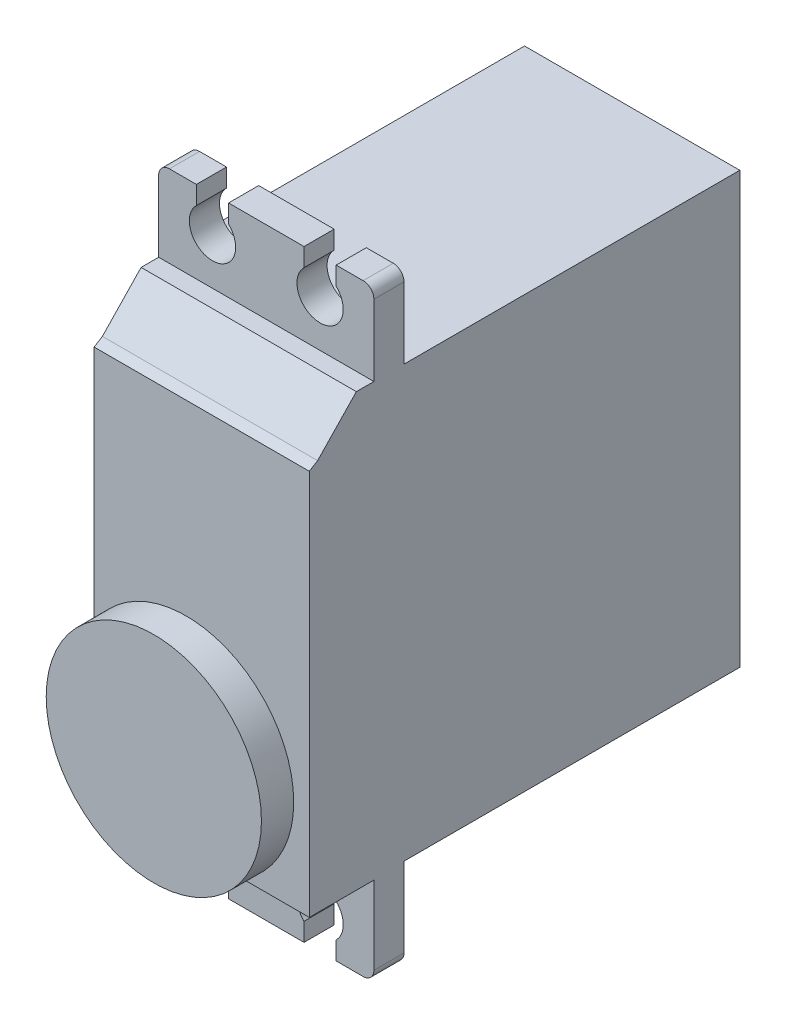
SolidWorks part; units mm, degrees
ref_plane "Front Plane" through (0, 0, 0) normal (0, 0, 1) x (1, 0, 0)
ref_plane "Top Plane" through (0, 0, 0) normal (0, 1, 0) x (1, 0, 0)
ref_plane "Right Plane" through (0, 0, 0) normal (1, 0, 0) x (0, 0, -1)
other "Configuration Table"
sketch "Sketch1" plane through (0, 0, 0) normal (0, 0, 1) x (1, 0, 0)
  line L0 (21.2784, 18.3365) -> (21.2784, 49.5365) construction
  line L1 (111.0279, 66.698) -> (111.0279, 64.6041) construction
  line L2 (101.0279, 10.698) -> (121.0279, 10.698)
  line L3 (101.0279, 10.698) -> (101.0279, 66.698)
  line L4 (101.0279, 66.698) -> (121.0279, 66.698)
  line L5 (121.0279, 10.698) -> (121.0279, 66.698)
  line L6 (101.0279, 38.698) -> (94.5146, 38.698) construction
  line L7 (106.0279, 13.948) -> (106.0279, 28.948) construction
  line L8 (111.0279, 10.698) -> (111.0279, 28.948) construction
  line L9 (106.0279, 28.948) -> (111.0279, 28.948) construction
  line L10 (104.5342, 10.698) -> (104.5342, 12.4)
  line L11 (107.5217, 10.698) -> (107.5217, 12.4)
  line L12 (114.5342, 10.698) -> (114.5342, 12.4)
  line L13 (117.5217, 10.698) -> (117.5217, 12.4)
  line L14 (104.5342, 66.698) -> (104.5342, 64.996)
  line L15 (107.5217, 66.698) -> (107.5217, 64.996)
  line L16 (114.5342, 66.698) -> (114.5342, 64.996)
  line L17 (117.5217, 66.698) -> (117.5217, 64.996)
  circle A0 centre (106.0279, 63.448) radius 2.1512
  circle A1 centre (116.0279, 63.448) radius 2.1512
  circle A2 centre (116.0279, 13.948) radius 2.1512
  circle A3 centre (106.0279, 13.948) radius 2.1512
  circle A4 centre (111.0279, 28.948) radius 2.7114
  line B0 (25.5393, 52.2674) -> (25.5393, 53.836)
  line B1 (30.5611, 18.2674) -> (70.5611, 18.2674)
  line B2 (30.5611, 18.2674) -> (30.5611, 49.4674)
  line B3 (30.5611, 49.4674) -> (70.5611, 49.4674)
  line B4 (70.5611, 18.2674) -> (70.5611, 49.4674)
  line B5 (25.5393, 53.836) -> (30.5611, 53.836)
  line B6 (30.5611, 53.836) -> (30.5611, 53.9)
  line B7 (30.5611, 53.9) -> (34.3144, 57.4974)
  line B8 (34.3144, 57.4974) -> (34.7849, 58.2674)
  line B9 (34.7849, 58.2674) -> (54.0071, 58.2674)
  line B10 (54.0071, 58.2674) -> (54.5684, 59.186)
  line B11 (54.5684, 59.186) -> (57.2514, 59.186)
  line B12 (57.2514, 59.186) -> (57.2514, 62.7174)
  line B13 (57.2514, 62.7174) -> (63.6958, 62.7174)
  line B14 (63.6958, 62.7174) -> (63.6958, 59.186)
  line B15 (63.6958, 59.186) -> (66.0527, 59.186)
  line B16 (66.0527, 59.186) -> (66.9468, 58.2674)
  line B17 (66.9468, 58.2674) -> (70.6846, 58.2674)
  line B18 (70.6846, 58.2674) -> (70.6846, 53.2324)
  line B19 (70.6846, 53.2324) -> (75.9568, 53.2324)
  line B20 (75.9568, 53.2324) -> (75.9568, 52.1823)
  line B21 (75.9568, 52.1823) -> (78.9446, 52.1823)
  line B22 (78.9446, 52.1823) -> (78.9446, 49.4674)
  line B23 (78.9446, 49.4674) -> (70.5611, 49.4674)
  line B24 (25.5393, 52.2674) -> (22.5513, 52.2674)
  line B25 (22.5513, 52.2674) -> (22.5513, 49.4674)
  line B26 (22.5513, 49.4674) -> (30.5611, 49.4674)
  dimension "D1" = 31.2
  dimension "D2" = 56
  dimension "D3" = 20
  dimension "D4" = 49.5
  dimension "D5" = 10
  dimension "D6" = 15
sketch_block_instance "Block1-1"
sketch_block "Block1" parameters "D1"=31.2, "D2"=2.8, "D3"=40, "D4"=44.45, "D5"=40.3776
extrude "Boss-Extrude2" add sketch "Sketch1" along normal blind 2.8 contours L10 A3 L11 L2 L12 A2 L13 L5 L4 L17 A1 L16 L15 A0 L14 L3 A4
fillet "Fillet1" radius 1 4 edges at (101.0279, 10.698, 1.4) (121.0279, 10.698, 1.4) (121.0279, 66.698, 1.4) (101.0279, 66.698, 1.4)
sketch "Sketch5" plane through (101.0279, 0, 0) normal (-1, 0, 0) x (0, 0, 1)
  line L3 (2.8, 10.698) -> (0, 10.698) construction
  line L4 (0, 10.698) -> (0, 66.698) construction
  line B0 (2.8, 64.1033) -> (4.3686, 64.1033)
  line B1 (-31.2, 59.0816) -> (-31.2, 19.0816)
  line B2 (-31.2, 59.0816) -> (0, 59.0816)
  line B3 (0, 59.0816) -> (0, 19.0816)
  line B4 (-31.2, 19.0816) -> (0, 19.0816)
  line B5 (4.3686, 64.1033) -> (4.3686, 59.0816)
  line B6 (4.3686, 59.0816) -> (4.4326, 59.0816)
  line B7 (4.4326, 59.0816) -> (8.03, 55.3283)
  line B8 (8.03, 55.3283) -> (8.8, 54.8577)
  line B9 (8.8, 54.8577) -> (8.8, 35.6356)
  line B10 (8.8, 35.6356) -> (9.7186, 35.0742)
  line B11 (9.7186, 35.0742) -> (9.7186, 32.3912)
  line B12 (9.7186, 32.3912) -> (13.25, 32.3912)
  line B13 (13.25, 32.3912) -> (13.25, 25.9469)
  line B14 (13.25, 25.9469) -> (9.7186, 25.9469)
  line B15 (9.7186, 25.9469) -> (9.7186, 23.59)
  line B16 (9.7186, 23.59) -> (8.8, 22.6958)
  line B17 (8.8, 22.6958) -> (8.8, 18.9581)
  line B18 (8.8, 18.9581) -> (3.765, 18.9581)
  line B19 (3.765, 18.9581) -> (3.765, 13.6859)
  line B20 (3.765, 13.6859) -> (2.7149, 13.6859)
  line B21 (2.7149, 13.6859) -> (2.7149, 10.698)
  line B22 (2.7149, 10.698) -> (0, 10.698)
  line B23 (0, 10.698) -> (0, 19.0816)
  line B24 (2.8, 64.1033) -> (2.8, 67.0913)
  line B25 (2.8, 67.0913) -> (0, 67.0913)
  line B26 (0, 67.0913) -> (0, 59.0816)
  line M9 (2.8, 11.698) -> (2.8, 65.698)
  line M11 (0, 65.698) -> (0, 11.698)
sketch_block_instance "Block1-2"
extrude "Boss-Extrude4" add sketch "Sketch5" against normal up to surface (20 mm away) contours B20 B19 B18 B17 B16 B15 B14 B13 B12 B11 B10 B9 B8 B7 B6 B5 B0 M9 | B1 B4 B2 M11 up to face at (121.0279, 38.698, 1.4)
sketch "Sketch6" plane through (0, 0, 2.8) normal (0, 0, -1) x (-1, 0, 0)
  line L1 (-113.979, 64.1033) -> (-118.0769, 64.1033)
  line L2 (-113.979, 64.1033) -> (-118.0769, 64.1033)
  line L3 (-103.979, 64.1033) -> (-108.0769, 64.1033)
  line L4 (-103.979, 64.1033) -> (-108.0769, 64.1033)
  line L5 (-118.1631, 13.6859) -> (-113.8928, 13.6859)
  line L6 (-118.1631, 13.6859) -> (-113.8928, 13.6859)
  line L7 (-108.1631, 13.6859) -> (-103.8928, 13.6859)
  line L8 (-108.1631, 13.6859) -> (-103.8928, 13.6859)
  arc A1 (-118.0769, 64.1033) -> (-113.979, 64.1033) centre (-116.0279, 63.448) ccw
  arc A2 (-118.0769, 64.1033) -> (-113.979, 64.1033) centre (-116.0279, 63.448) ccw
  arc A3 (-108.0769, 64.1033) -> (-103.979, 64.1033) centre (-106.0279, 63.448) ccw
  arc A4 (-108.0769, 64.1033) -> (-103.979, 64.1033) centre (-106.0279, 63.448) ccw
  arc A5 (-113.8928, 13.6859) -> (-118.1631, 13.6859) centre (-116.0279, 13.948) ccw
  arc A6 (-113.8928, 13.6859) -> (-118.1631, 13.6859) centre (-116.0279, 13.948) ccw
  arc A7 (-103.8928, 13.6859) -> (-108.1631, 13.6859) centre (-106.0279, 13.948) ccw
  arc A8 (-103.8928, 13.6859) -> (-108.1631, 13.6859) centre (-106.0279, 13.948) ccw
  dimension "D1" = 0
  dimension "D2" = 0
  dimension "D3" = 0
  dimension "D4" = 0
extrude "Cut-Extrude1" cut sketch "Sketch6" against normal through all
sketch "Sketch7" plane through (0, 0, 2.8) normal (0, 0, 1) x (1, 0, 0)
  line L0 (121.0279, 59.0816) -> (101.0279, 59.0816) construction
  line L1 (95.4158, 68.4693) -> (125.1022, 68.4693)
  line L2 (95.4158, 68.4693) -> (95.4158, 59.0816)
  line L3 (95.4158, 59.0816) -> (125.1022, 59.0816)
  line L4 (125.1022, 68.4693) -> (125.1022, 59.0816)
  line L5 (121.0279, 18.9581) -> (101.0279, 18.9581) construction
  line L6 (97.5669, 8.7834) -> (125.1022, 8.7834)
  line L7 (97.5669, 8.7834) -> (97.5669, 18.9581)
  line L8 (97.5669, 18.9581) -> (125.1022, 18.9581)
  line L9 (125.1022, 8.7834) -> (125.1022, 18.9581)
extrude "Cut-Extrude2" cut sketch "Sketch7" along normal through all
sketch "Sketch8" plane through (101.0279, 0, 0) normal (-1, 0, 0) x (0, 0, 1)
  line L0 (8.8, 54.8577) -> (8.8, 35.6356) construction
  line L1 (8.8, 37.3713) -> (16.237, 37.3713)
  line L2 (8.8, 37.3713) -> (8.8, 20.8586)
  line L3 (8.8, 20.8586) -> (16.237, 20.8586)
  line L4 (16.237, 37.3713) -> (16.237, 20.8586)
sketch "Sketch9" plane through (0, 0, 8.8) normal (0, 0, 1) x (1, 0, 0)
  circle A0 centre (111.0279, 28.948) radius 3.5276
extrude "Boss-Extrude5" add sketch "Sketch9" along normal through all separate body
extrude "Cut-Extrude4" cut sketch "Sketch8" against normal through all
sketch "Sketch11" plane through (0, 0, 8.8) normal (0, 0, 1) x (1, 0, 0)
  circle A0 centre (111.0279, 28.948) radius 5
  dimension "D1" = 10
extrude "Boss-Extrude6" add sketch "Sketch11" along normal blind 1.45
sketch "Sketch12" plane through (0, 0, 10.25) normal (0, 0, 1) x (1, 0, 0)
  circle A0 centre (111.0279, 28.948) radius 10
  dimension "D1" = 20
extrude "Boss-Extrude7" add sketch "Sketch12" along normal blind 3
sketch "Sketch13" plane through (0, 0, 0) normal (0, 0, -1) x (-1, 0, 0)
  line L0 (-101.0279, 17.948) -> (-121.0279, 17.948)
  line L1 (-101.0279, 11.698) -> (-101.0279, 19.0816) construction
  line L2 (-121.0279, 11.698) -> (-121.0279, 19.0816) construction
  line L3 (-121.0279, 17.948) -> (-121.0279, 59.448)
  line L4 (-121.0279, 59.0816) -> (-121.0279, 65.698) construction
  line L5 (-121.0279, 59.448) -> (-101.0279, 59.448)
  line L6 (-101.0279, 59.0816) -> (-101.0279, 65.698) construction
  line L7 (-101.0279, 59.448) -> (-101.0279, 67.448)
  line L8 (-101.0279, 67.448) -> (-130.0279, 67.448)
  line L9 (-130.0279, 67.448) -> (-130.0279, 9.948)
  line L10 (-130.0279, 9.948) -> (-101.0279, 9.948)
  line L11 (-101.0279, 9.948) -> (-101.0279, 17.948)
  circle A0 centre (-116.0279, 13.948) radius 2
  circle A1 centre (-106.0279, 13.948) radius 2
  circle A2 centre (-116.0279, 63.448) radius 2
  circle A3 centre (-106.0279, 63.448) radius 2
  dimension "D1" = 4
  dimension "D2" = 4
  dimension "D3" = 4
  dimension "D4" = 4
  dimension "D5" = 4
  dimension "D6" = 9
